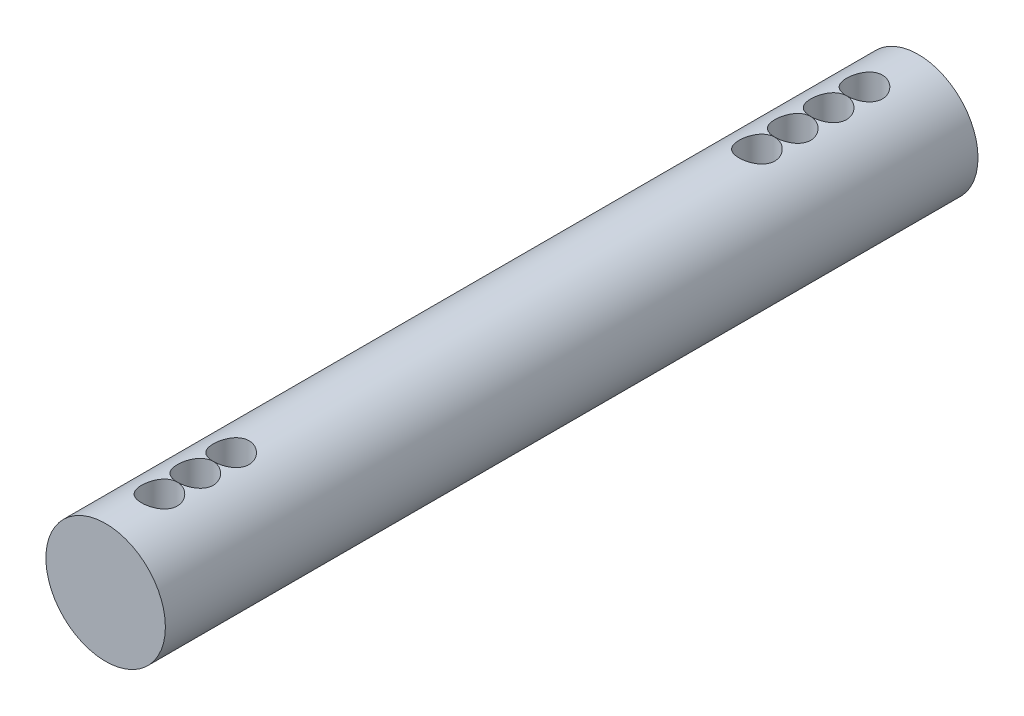
SolidWorks part; units mm, degrees
material "Alumina"
ref_plane "Front Plane" through (0, 0, 0) normal (0, 0, 1) x (1, 0, 0)
ref_plane "Top Plane" through (0, 0, 0) normal (0, 1, 0) x (1, 0, 0)
ref_plane "Right Plane" through (0, 0, 0) normal (1, 0, 0) x (0, 0, -1)
sketch "Sketch1" plane through (0, 0, 0) normal (0, 0, 1) x (1, 0, 0)
  circle A0 centre (0, 0) radius 5
  dimension "D1" = 10
extrude "Boss-Extrude1" add sketch "Sketch1" along normal mid plane 68
sketch "Sketch2" plane through (0, 0, 0) normal (0, 1, 0) x (1, 0, 0)
  line L1 (-5, -31) -> (5, -31) construction
  line L2 (-5, 34) -> (-5, -34) construction
  line L3 (5, -34) -> (5, 34) construction
  line L4 (-5, -34) -> (5, -34) construction
  circle A1 centre (0, -29.5) radius 1.5
  dimension "D1" = 3
  dimension "D2" = 3
extrude "Cut-Extrude1" cut sketch "Sketch2" against normal through all both and the other way through all from offset 5
pattern_linear "LPattern3" count 3 spacing 3.001 along (0, 0, -1) of "Cut-Extrude1"
sketch "Sketch3" plane through (0, 0, 0) normal (0, 1, 0) x (1, 0, 0)
  line L0 (5, 31) -> (-5, 31) construction
  line L1 (5, -34) -> (5, 34) construction
  line L2 (-5, 34) -> (-5, -34) construction
  line L3 (5, 34) -> (-5, 34) construction
  circle A0 centre (0, 29.5) radius 1.5
  dimension "D1" = 3
  dimension "D2" = 3
extrude "Cut-Extrude2" cut sketch "Sketch3" against normal through all both and the other way through all from offset 5
pattern_linear "LPattern4" count 4 spacing 3.001 along (0, 0, 1) of "Cut-Extrude2"
equation "\"shaft_diameter\"=10"
equation "\"key_diameter\"=3"
equation "\"key_front_number\"= 3"
equation "\"key_distance_front\"= 3"
equation "\"key_distance_back\"= 3"
equation "\"key_depth\"=3"
equation "\"D1@Sketch1\"=\"shaft_diameter\""
equation "\"D1@Boss-Extrude1\"= \"key_distance_front\" + ( \"key_front_number\" * \"key_diameter\" ) + \"key_gap\" + ( \"key_back_number\" * \"key_diameter\" ) + \"key_distance_back\""
equation "\"D1@Sketch2\"=\"key_diameter\""
equation "\"key_height\"=1.5"
equation "\"D2@Sketch2\"=\"key_distance_front\""
equation "\"D19@Cut-Extrude1\"=\"shaft_diameter\" / 2"
equation "\"D1@LPattern3\"=\"key_front_number\""
equation "\"D3@LPattern3\"=\"key_diameter\" + 0.001"
equation "\"key_back_number\"= 4"
equation "\"key_gap\"= 41"
equation "\"D1@Sketch3\"=\"key_distance_back\""
equation "\"D2@Sketch3\"=\"key_diameter\""
equation "\"D19@Cut-Extrude2\"=\"shaft_diameter\" / 2"
equation "\"D1@Cut-Extrude2\"=\"key_depth\""
equation "\"D3@LPattern4\"=\"key_diameter\" + 0.001"
equation "\"D1@LPattern4\"=\"key_back_number\""
